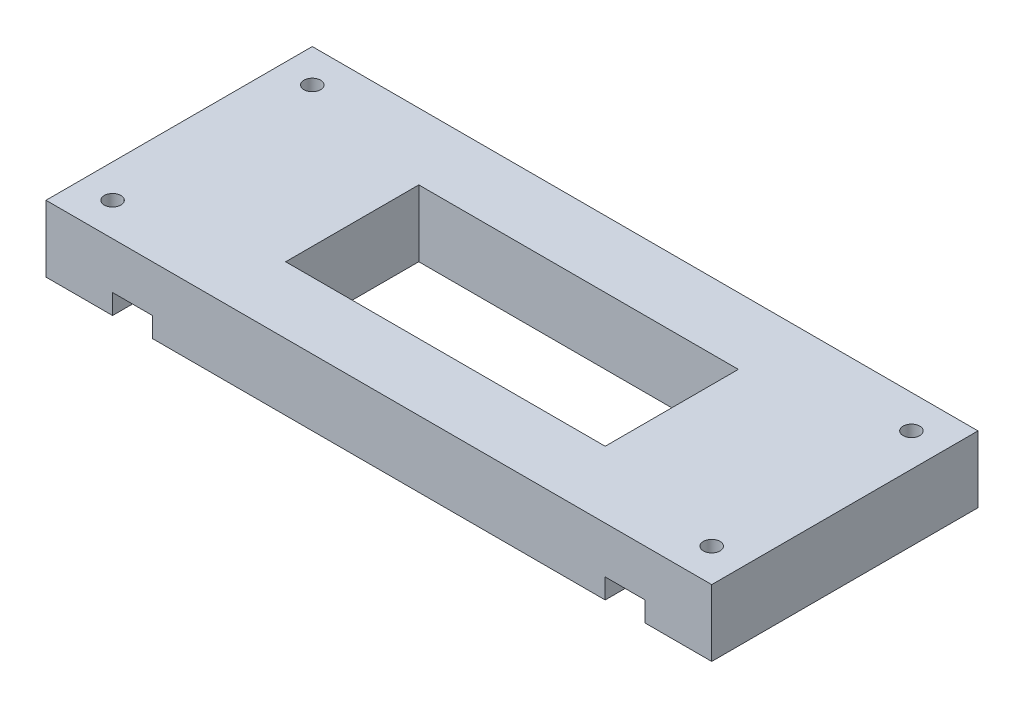
SolidWorks part; units mm, degrees
ref_plane "Plan de face" through (0, 0, 0) normal (0, 0, 1) x (1, 0, 0)
ref_plane "Plan de dessus" through (0, 0, 0) normal (0, 1, 0) x (1, 0, 0)
ref_plane "Plan de droite" through (0, 0, 0) normal (1, 0, 0) x (0, 0, -1)
sketch "Esquisse1" plane through (0, 0, 0) normal (0, 0, 1) x (1, 0, 0)
  line L0 (0, 0) -> (10, 0)
  line L1 (0, 10) -> (100, 10)
  line L2 (0, 10) -> (0, 0)
  line L3 (100, 10) -> (100, 0)
  line L4 (10, 0) -> (10, 3)
  line L5 (10, 3) -> (16, 3)
  line L6 (16, 3) -> (16, 0)
  line L7 (16, 0) -> (84, 0)
  line L8 (84, 0) -> (84, 3)
  line L9 (84, 3) -> (90, 3)
  line L10 (90, 3) -> (90, 0)
  line L11 (90, 0) -> (100, 0)
  dimension "D1" = 10
  dimension "D2" = 100
  dimension "D3" = 3
  dimension "D4" = 6
  dimension "D5" = 10
extrude "Boss.-Extru.1" add sketch "Esquisse1" along normal blind 40
sketch "Esquisse2" plane through (0, 10, 0) normal (0, 1, 0) x (1, 0, 0)
  line L1 (26, -10) -> (74, -10)
  line L2 (26, -10) -> (26, -30)
  line L3 (26, -30) -> (74, -30)
  line L4 (74, -10) -> (74, -30)
  line L5 (16, -40) -> (16, 0) construction
  line L6 (16, -40) -> (84, -40) construction
  line L7 (16, -40) -> (16, 0) construction
  line L8 (16, -40) -> (84, -40) construction
  point P8 (26, -20)
  point P9 (16, -20)
  point P10 (50, -40)
  point P11 (50, -30)
  dimension "D1" = 10
  dimension "D2" = 10
extrude "Enlèv. mat.-Extru.1" cut sketch "Esquisse2" against normal up to next
sketch "Esquisse3" plane through (0, 0, 0) normal (0, -1, 0) x (1, 0, 0)
  line L0 (0, 40) -> (10, 40) construction
  line L1 (90, 40) -> (100, 40) construction
  line L2 (5, 35) -> (5, 5) construction
  line L3 (0, 40) -> (0, 0) construction
  circle A0 centre (5, 35) radius 1.25
  circle A1 centre (5, 5) radius 1.25
  circle A2 centre (95, 35) radius 1.25
  circle A3 centre (95, 5) radius 1.25
  point P8 (5, 20)
  point P11 (5, 40)
  point P14 (0, 20)
  point P17 (95, 40)
  dimension "D2" = 2.5
  dimension "D1" = 30
extrude "Enlèv. mat.-Extru.2" cut sketch "Esquisse3" against normal up to next
